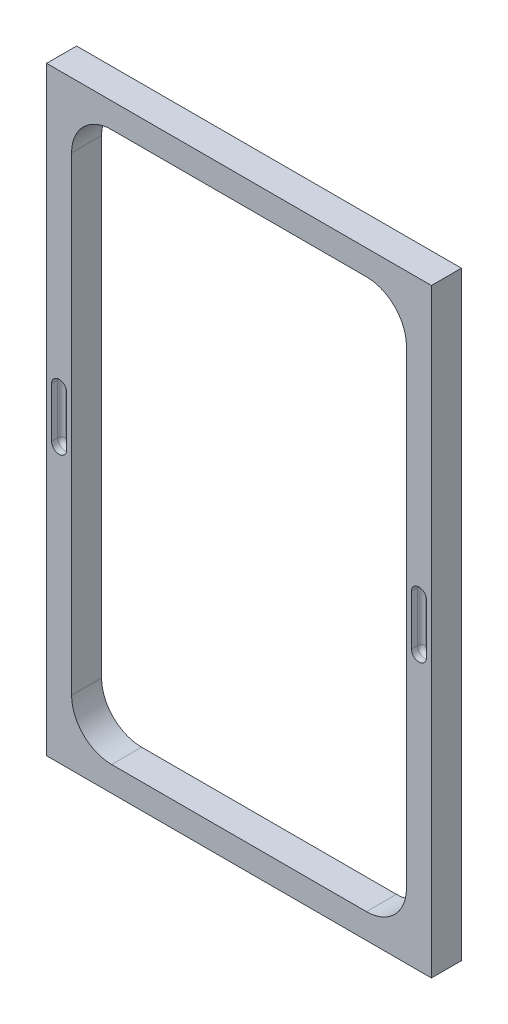
SolidWorks part; units mm, degrees
ref_plane "Front Plane" through (0, 0, 0) normal (0, 0, 1) x (1, 0, 0)
ref_plane "Top Plane" through (0, 0, 0) normal (0, 1, 0) x (1, 0, 0)
ref_plane "Right Plane" through (0, 0, 0) normal (1, 0, 0) x (0, 0, -1)
sketch "Sketch1" plane through (0, 0, 0) normal (0, 0, 1) x (1, 0, 0)
  line L0 (63.5, 165.1) -> (63.5, 1358.9)
  line L1 (0, 0) -> (977.9, 0)
  line L2 (0, 0) -> (0, 1524)
  line L3 (0, 1524) -> (977.9, 1524)
  line L4 (977.9, 0) -> (977.9, 1524)
  line L5 (165.1, 1460.5) -> (812.8, 1460.5)
  line L6 (914.4, 165.1) -> (914.4, 1358.9)
  line L7 (165.1, 63.5) -> (812.8, 63.5)
  line L8 (63.5, 63.5) -> (63.5, 1460.5) construction
  line L9 (63.5, 63.5) -> (914.4, 63.5) construction
  line L10 (914.4, 63.5) -> (914.4, 1460.5) construction
  line L11 (63.5, 1460.5) -> (914.4, 1460.5) construction
  arc A0 (63.5, 165.1) -> (165.1, 63.5) centre (165.1, 165.1) ccw
  arc A1 (914.4, 165.1) -> (812.8, 63.5) centre (812.8, 165.1) cw
  arc A2 (812.8, 1460.5) -> (914.4, 1358.9) centre (812.8, 1358.9) cw
  arc A3 (63.5, 1358.9) -> (165.1, 1460.5) centre (165.1, 1358.9) cw
  dimension "D4" = 101.6
  dimension "D1" = 977.9
  dimension "D2" = 1524
  dimension "D3" = 63.5
extrude "Boss-Extrude1" add sketch "Sketch1" along normal blind 76.2
sketch "Sketch2" plane through (0, 0, 76.2) normal (0, 0, 1) x (1, 0, 0)
  line L0 (31.75, 825.5) -> (31.75, 698.5) construction
  line L1 (50.8, 825.5) -> (50.8, 698.5)
  line L2 (12.7, 825.5) -> (12.7, 698.5)
  line L3 (63.5, 1358.9) -> (63.5, 165.1) construction
  line L4 (914.4, 165.1) -> (914.4, 1358.9) construction
  line L5 (488.95, 1524) -> (488.95, 969.2113) construction
  line L6 (977.9, 1524) -> (0, 1524) construction
  line L7 (946.15, 825.5) -> (946.15, 698.5) construction
  line L8 (927.1, 825.5) -> (927.1, 698.5)
  line L9 (965.2, 825.5) -> (965.2, 698.5)
  arc A0 (50.8, 825.5) -> (12.7, 825.5) centre (31.75, 825.5) ccw
  arc A1 (12.7, 698.5) -> (50.8, 698.5) centre (31.75, 698.5) ccw
  arc A2 (927.1, 825.5) -> (965.2, 825.5) centre (946.15, 825.5) cw
  arc A3 (965.2, 698.5) -> (927.1, 698.5) centre (946.15, 698.5) cw
  point P2 (31.75, 762)
  point P13 (914.4, 762)
  point P18 (946.15, 762)
  dimension "D3" = 127
  dimension "D1" = 12.7
  dimension "D2" = 38.1
extrude "Cut-Extrude1" cut sketch "Sketch2" against normal blind 25.4
fillet "Fillet1" radius 10.16 8 edges at (965.2, 762, 50.8) (946.15, 679.45, 50.8) (927.1, 762, 50.8) (946.15, 844.55, 50.8) (50.8, 762, 50.8) (31.75, 679.45, 50.8) (12.7, 762, 50.8) (31.75, 844.55, 50.8)
